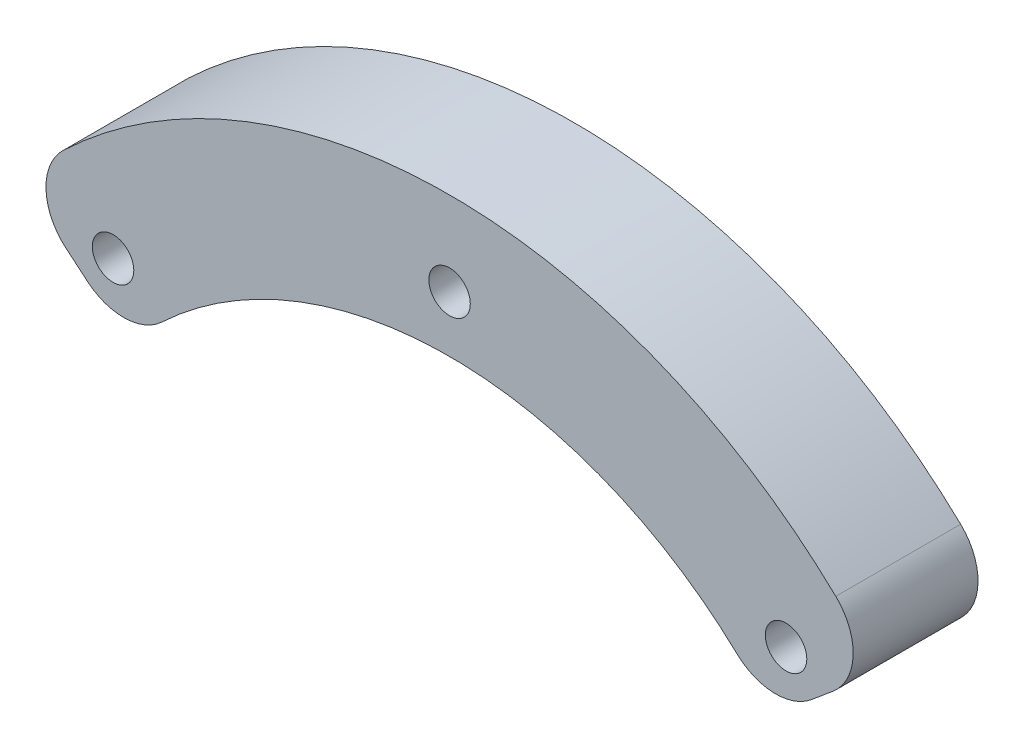
SolidWorks part; units mm, degrees
ref_plane "前视基准面" through (0, 0, 0) normal (0, 0, 1) x (1, 0, 0)
ref_plane "上视基准面" through (0, 0, 0) normal (0, 1, 0) x (1, 0, 0)
ref_plane "右视基准面" through (0, 0, 0) normal (1, 0, 0) x (0, 0, -1)
other "Configuration Table"
sketch "草图1" plane through (0, 0, 0) normal (0, 0, 1) x (1, 0, 0)
  line L0 (0, 0) -> (38.3022, 32.1394)
  line L1 (0, 0) -> (-38.3022, 32.1394)
  line L2 (0, 50) -> (0, -50) construction
  circle A0 centre (0, 0) radius 50
  circle A1 centre (0, 0) radius 37.5
  circle A2 centre (42.5, 0) radius 1.85
  circle A3 centre (30.052, -30.052) radius 1.85
  circle A4 centre (0, -42.5) radius 1.85
  circle A5 centre (-30.052, -30.052) radius 1.85
  circle A6 centre (-42.5, 0) radius 1.85
  circle A7 centre (-30.052, 30.052) radius 1.85
  circle A8 centre (0, 42.5) radius 1.85
  circle A9 centre (30.052, 30.052) radius 1.85
  point P23 (0, 0)
  dimension "D1" = 100
  dimension "D2" = 75
  dimension "D3" = 3.7
  dimension "D4" = 42.5
  dimension "D6" = 50
  dimension "D7" = 50
  dimension "D5" = 8
extrude "凸台-拉伸1" add sketch "草图1" along normal blind 11.15 contours L2 A0 L1 A1 A8 A7 | A0 L2 A8 A1 L0 A9
fillet "圆角3" radius 5 4 edges at (38.3022, 32.1394, 5.575) (28.7267, 24.1045, 5.575) (-28.7267, 24.1045, 5.575) (-38.3022, 32.1394, 5.575)
